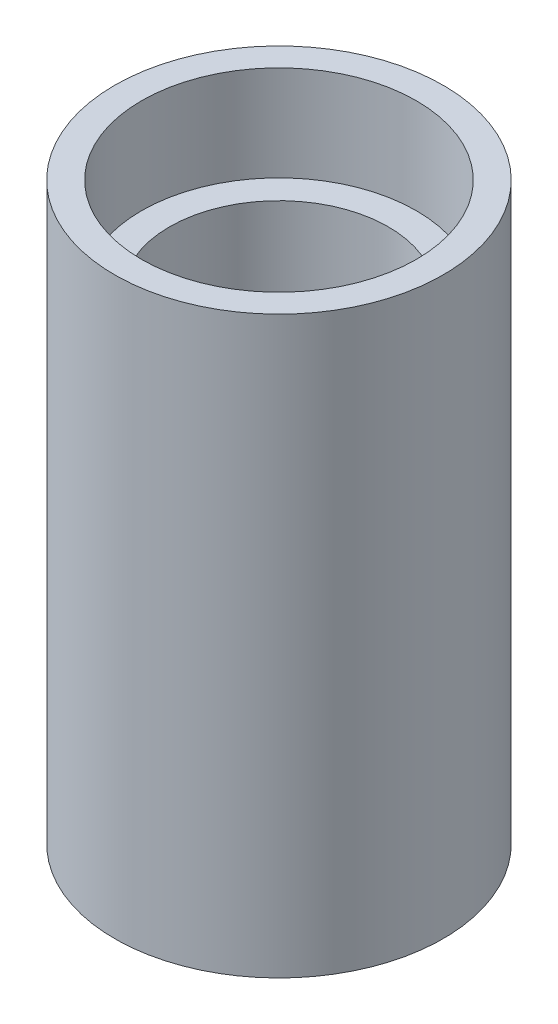
SolidWorks part; units mm, degrees
material "6061-T6 (SS)"
ref_plane "Front Plane" through (0, 0, 0) normal (0, 0, 1) x (1, 0, 0)
ref_plane "Top Plane" through (0, 0, 0) normal (0, 1, 0) x (1, 0, 0)
ref_plane "Right Plane" through (0, 0, 0) normal (1, 0, 0) x (0, 0, -1)
sketch "Sketch1" plane through (0, 0, 0) normal (0, 0, 1) x (1, 0, 0)
  line L0 (0, 55.7468) -> (0, -29.699) construction
  line L2 (25.4, 0) -> (38.1, 0)
  line L3 (25.4, 0) -> (25.4, 111.252)
  line L4 (31.877, 133.35) -> (38.1, 133.35)
  line L5 (38.1, 0) -> (38.1, 133.35)
  line L8 (25.4, 111.252) -> (31.877, 111.252)
  line L9 (31.877, 133.35) -> (31.877, 111.252)
  dimension "D1" = 76.2
  dimension "D2" = 12.7
  dimension "D3" = 133.35
  dimension "D4" = 22.098
  dimension "D5" = 63.754
revolve "Revolve1" add sketch "Sketch1" angle 360 about L0
